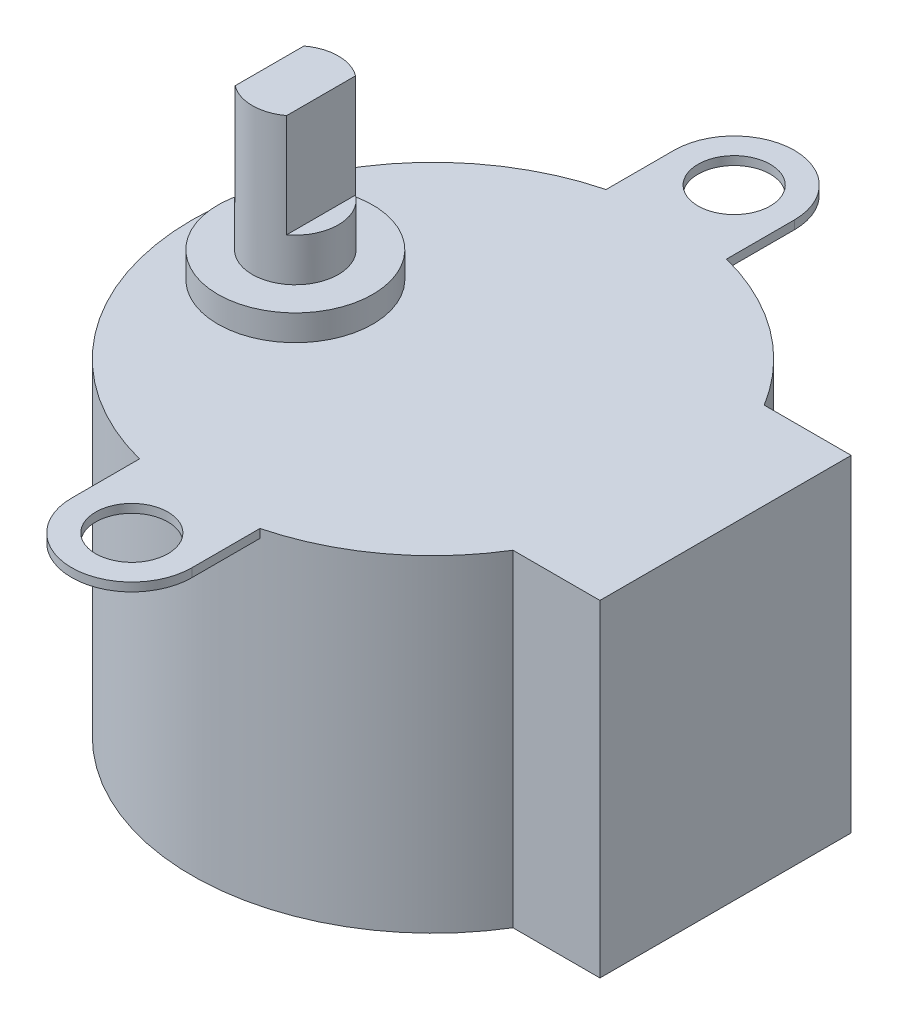
SolidWorks part; units mm, degrees
ref_plane "Front Plane" through (0, 0, 0) normal (0, 0, 1) x (1, 0, 0)
ref_plane "Top Plane" through (0, 0, 0) normal (0, 1, 0) x (1, 0, 0)
ref_plane "Right Plane" through (0, 0, 0) normal (1, 0, 0) x (0, 0, -1)
sketch "Sketch1" plane through (0, 0, 0) normal (0, 1, 0) x (1, 0, 0)
  line L1 (11.9461, 7.3) -> (17, 7.3)
  line L3 (11.9461, -7.3) -> (17, -7.3)
  line L4 (17, 7.3) -> (17, -7.3)
  arc A0 (11.9461, 7.3) -> (11.9461, -7.3) centre (0, 0) ccw
  dimension "D1" = 28
  dimension "D2" = 17
  dimension "D3" = 14.6
extrude "Boss-Extrude1" add sketch "Sketch1" along normal blind 19
sketch "Sketch3" plane through (0, 19, 0) normal (0, 1, 0) x (1, 0, 0)
  line L0 (0, 17.5) -> (0, -17.5) construction
  line L1 (3.5, 17.5) -> (3.5, -17.5)
  line L2 (-3.5, 17.5) -> (-3.5, -17.5)
  arc A0 (3.5, 17.5) -> (-3.5, 17.5) centre (0, 17.5) ccw
  arc A1 (-3.5, -17.5) -> (3.5, -17.5) centre (0, -17.5) ccw
  circle A2 centre (0, -17.5) radius 2.1
  circle A3 centre (0, 17.5) radius 2.1
  point P2 (0, 0)
  dimension "D2" = 4.2
  dimension "D1" = 7
  dimension "D3" = 35
extrude "Boss-Extrude2" add sketch "Sketch3" against normal blind 0.5
sketch "Sketch4" plane through (0, 19, 0) normal (0, 1, 0) x (1, 0, 0)
  circle A0 centre (-8, 0) radius 4.5
  dimension "D2" = 9
  dimension "D1" = 8
extrude "Boss-Extrude3" add sketch "Sketch4" along normal blind 1.5
sketch "Sketch5" plane through (0, 20.5, 0) normal (0, 1, 0) x (1, 0, 0)
  circle A0 centre (-8, 0) radius 2.5
  dimension "D1" = 5
extrude "Boss-Extrude4" add sketch "Sketch5" along normal blind 8.5
sketch "Sketch6" plane through (0, 29, 0) normal (0, 1, 0) x (1, 0, 0)
  line L0 (-9.5, 0) -> (-6.5, 0) construction
  line L2 (-9.5, 2) -> (-9.5, -2)
  line L4 (-6.5, 2) -> (-6.5, -2)
  circle A1 centre (-8, 0) radius 2.5 construction
  arc A2 (-9.5, 2) -> (-9.5, -2) centre (-8, 0) ccw
  arc A3 (-6.5, -2) -> (-6.5, 2) centre (-8, 0) ccw
  dimension "D1" = 3
extrude "Cut-Extrude1" cut sketch "Sketch6" against normal blind 6
